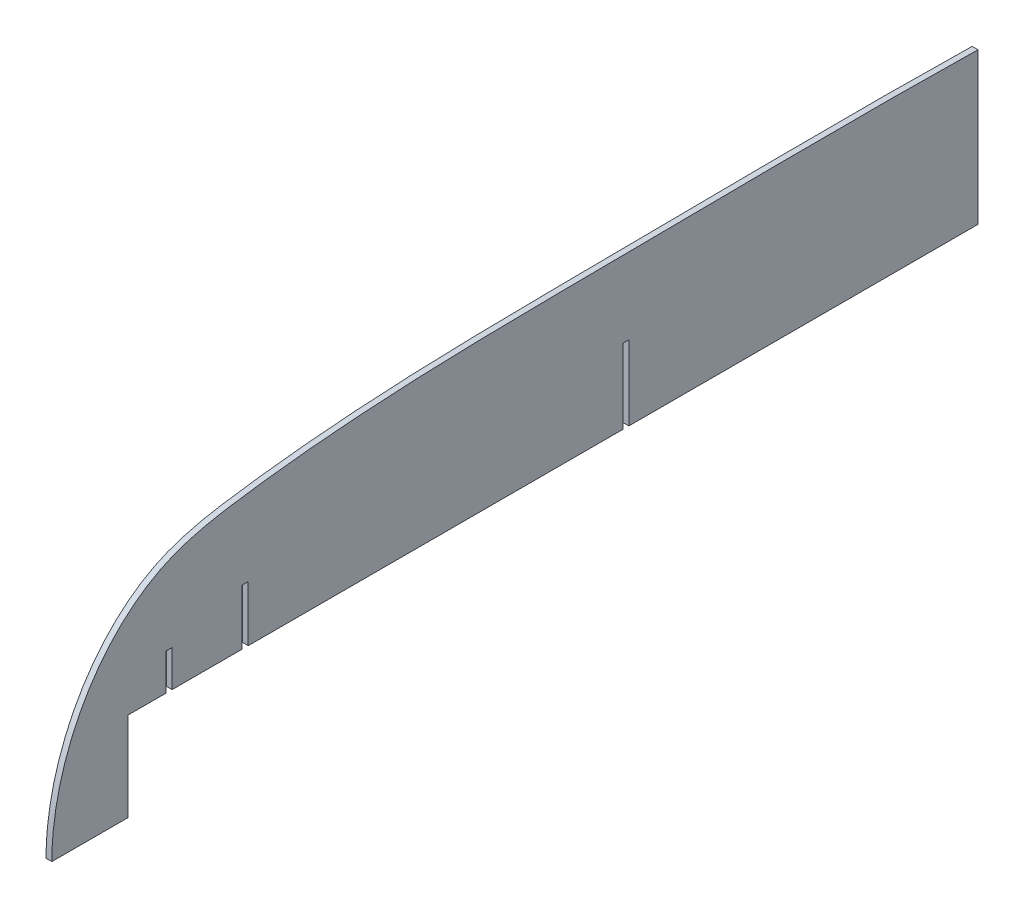
SolidWorks part; units mm, degrees
ref_plane "Front" through (0, 0, 0) normal (0, 0, 1) x (1, 0, 0)
ref_plane "Top" through (0, 0, 0) normal (0, 1, 0) x (1, 0, 0)
ref_plane "Right" through (0, 0, 0) normal (1, 0, 0) x (0, 0, -1)
sketch "Sketch2" plane through (0, 0, 0) normal (1, 0, 0) x (0, 0, -1)
  line L0 (-1460.5, 39.6875) -> (-1460.5, 349.9239) construction
  line L1 (381, 39.6875) -> (381, 279.4) construction
  spline S0 degree 3 poles (-1460.5, 39.6875) (-1460.5, 123.8546) (-1400.449, 238.6436) (-1168.2645, 278.6532) (-889.8632, 278.1926) (-549.517, 284.0694) (-254.873, 268.1625) (-19.654, 247.7534) (192.8383, 207.087) (381, 130.9866) (381, 39.6875) knots 0 0 0 0 0.114448 0.153235 0.341616 0.529763 0.65535 0.781407 0.871202 1 1 1 1
sketch "Sketch3" plane through (0, 0, 0) normal (1, 0, 0) x (0, 0, -1)
  line L0 (-1460.5, 39.6875) -> (381, 39.6875)
  spline S0 degree 3 poles (2306.188, 3048.0378) (-1409.0131, -1518.6462) (-1723.3281, 183.0057) (-1168.2645, 278.6532) (-889.8632, 278.1926) (-549.517, 284.0694) (-254.873, 268.1625) (-19.654, 247.7534) (398.4735, 167.7329) (1079.4836, -218.359) (-4096.3718, -2107.6866) knots -0.475057 -0.475057 -0.475057 -0.475057 0.114448 0.153235 0.341616 0.529763 0.65535 0.781407 0.871202 1.333528 1.333528 1.333528 1.333528 only from (-1460.5, 39.6875) to (381, 39.6875) construction
  spline S1 degree 3 poles (-1460.5, 39.6875) (-1460.5, 123.8546) (-1400.449, 238.6436) (-1168.2645, 278.6532) (-889.8632, 278.1926) (-549.517, 284.0694) (-254.873, 268.1625) (-19.654, 247.7534) (192.8383, 207.087) (381, 130.9866) (381, 39.6875) knots 0 0 0 0 0.114448 0.153235 0.341616 0.529763 0.65535 0.781407 0.871202 1 1 1 1
extrude "Boss-Extrude1" add sketch "Sketch3" along normal mid plane 5.842
sketch "Sketch5" plane through (2.921, 0, 0) normal (1, 0, 0) x (0, 0, -1)
  line L0 (-1460.5, 39.6875) -> (381, 39.6875) construction
  line L1 (-1384.3, 39.6875) -> (545.9156, 39.6875)
  line L2 (-1384.3, 39.6875) -> (-1384.3, 128.5875)
  line L3 (-1384.3, 128.5875) -> (-1346.2, 128.5875)
  line L4 (-1346.2, 165.1) -> (-1346.2, 128.5875)
  line L5 (-533.4, 128.5875) -> (-533.4, 328.8563)
  line L6 (-533.4, 328.8563) -> (545.9156, 328.8563)
  line L7 (545.9156, 328.8563) -> (545.9156, 39.6875)
  line L8 (-1340.104, 165.1) -> (-1340.104, 128.5875)
  line L9 (-1346.2, 165.1) -> (-1346.2, 241.3) construction
  line L10 (-1346.2, 165.1) -> (-1340.104, 165.1)
  line L11 (-1340.104, 128.5875) -> (-1270, 128.5875)
  line L12 (-1270, 184.15) -> (-1270, 128.5875)
  line L13 (-1270, 260.35) -> (-1270, 184.15) construction
  line L14 (-1270, 184.15) -> (-1263.904, 184.15)
  line L15 (-889, 203.2) -> (-889, 128.5875)
  line L16 (-1263.904, 184.15) -> (-1263.904, 128.5875)
  line L17 (-889, 279.4) -> (-889, 203.2) construction
  line L18 (-889, 203.2) -> (-882.904, 203.2)
  line L20 (-1263.904, 128.5875) -> (-889, 128.5875)
  line L21 (-882.904, 203.2) -> (-882.904, 128.5875)
  line L22 (-882.904, 128.5875) -> (-533.4, 128.5875)
  point P11 (-503.5538, 128.5875)
  dimension "D1" = 88.9
  dimension "D2" = 25.4
  dimension "D3" = 1384.3
  dimension "D4" = 76.2
  dimension "D5" = 76.2
  dimension "D6" = 6.096
  dimension "D7" = 6.096
  dimension "D8" = 6.096
  dimension "D9" = 76.2
extrude "Cut-Extrude1" cut sketch "Sketch5" against normal through all
